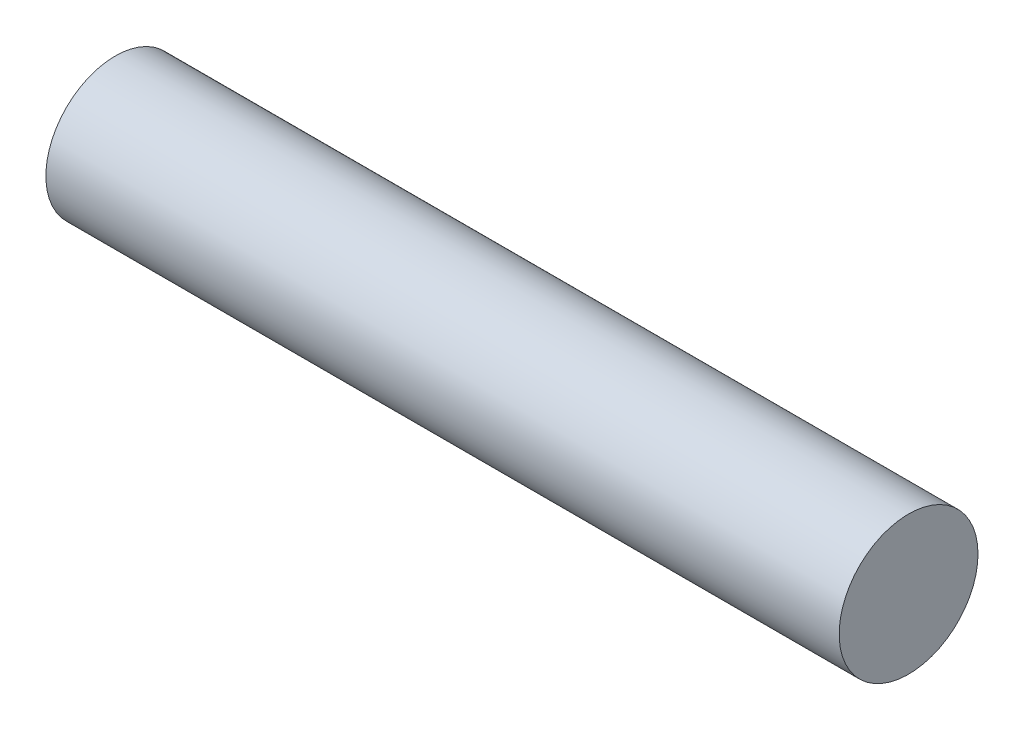
SolidWorks part; units mm, degrees
material "Серое литое железо (SN)"
ref_plane "Спереди" through (0, 0, 0) normal (0, 0, 1) x (1, 0, 0)
ref_plane "Сверху" through (0, 0, 0) normal (0, 1, 0) x (1, 0, 0)
ref_plane "Справа" through (0, 0, 0) normal (1, 0, 0) x (0, 0, -1)
sketch "Эскиз1" plane through (0, 0, 0) normal (1, 0, 0) x (0, 0, -1)
  circle A0 centre (0, 0) radius 1.75
  dimension "D1" = 3.5
extrude "Бобышка-Вытянуть1" add sketch "Эскиз1" along normal blind 20
